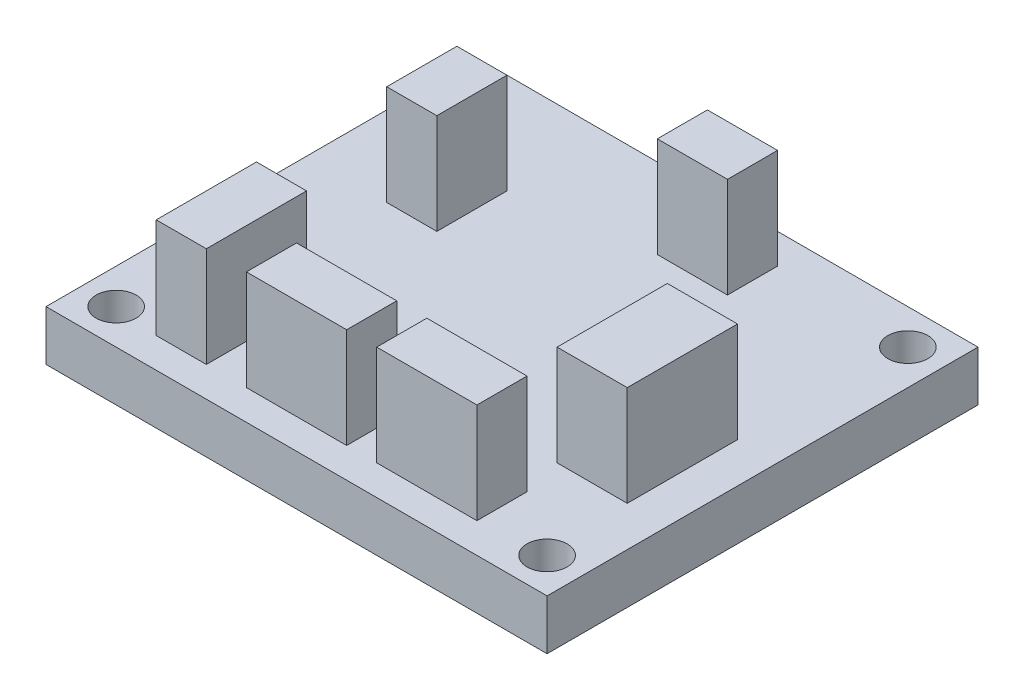
SolidWorks part; units mm, degrees
ref_plane "Plan de face" through (0, 0, 0) normal (0, 0, 1) x (1, 0, 0)
ref_plane "Plan de dessus" through (0, 0, 0) normal (0, 1, 0) x (1, 0, 0)
ref_plane "Plan de droite" through (0, 0, 0) normal (1, 0, 0) x (0, 0, -1)
sketch "Esquisse1" plane through (0, 0, 0) normal (0, 1, 0) x (1, 0, 0)
  line L0 (-25, 0) -> (0, 0) construction
  line L1 (-25, -21.5) -> (25, -21.5)
  line L2 (-25, -21.5) -> (-25, 21.5)
  line L3 (-25, 21.5) -> (25, 21.5)
  line L4 (25, -21.5) -> (25, 21.5)
  line L7 (0, 0) -> (0, 21.5) construction
  circle A0 centre (-21.5, 18) radius 2
  circle A1 centre (21.5, 18) radius 2
  circle A2 centre (21.5, -18) radius 2
  circle A3 centre (-21.5, -18) radius 2
  circle A4 centre (-21.5, 18) radius 3.5 construction
  dimension "D3" = 4
  dimension "D4" = 3.5
  dimension "D5" = 36
  dimension "D6" = 43
  dimension "D1" = 43
  dimension "D2" = 50
extrude "Boss.-Extru.1" add sketch "Esquisse1" along normal blind 5
sketch "Esquisse2" plane through (0, 0, 0) normal (0, 1, 0) x (1, 0, 0)
  line L0 (-25, -21.5) -> (25, -21.5) construction
  line L1 (-17, -8.5) -> (-12, -8.5)
  line L2 (-17, -8.5) -> (-17, -18.5)
  line L3 (-17, -18.5) -> (-12, -18.5)
  line L4 (-12, -8.5) -> (-12, -18.5)
  line L5 (-17, 11.5) -> (-12, 11.5)
  line L6 (-17, 11.5) -> (-17, 4.5)
  line L7 (-17, 4.5) -> (-12, 4.5)
  line L8 (-12, 11.5) -> (-12, 4.5)
  line L9 (1, 18.5) -> (8, 18.5)
  line L10 (1, 18.5) -> (1, 13.5)
  line L11 (1, 13.5) -> (8, 13.5)
  line L12 (8, 18.5) -> (8, 13.5)
  line L13 (14, 1.5) -> (21, 1.5)
  line L14 (14, 1.5) -> (14, -9.5)
  line L15 (14, -9.5) -> (21, -9.5)
  line L16 (21, 1.5) -> (21, -9.5)
  line L17 (15, -13.5) -> (5, -13.5)
  line L18 (15, -13.5) -> (15, -18.5)
  line L19 (15, -18.5) -> (5, -18.5)
  line L20 (5, -13.5) -> (5, -18.5)
  line L21 (2, -18.5) -> (-8, -18.5)
  line L22 (2, -18.5) -> (2, -13.5)
  line L23 (2, -13.5) -> (-8, -13.5)
  line L24 (-8, -18.5) -> (-8, -13.5)
  line L25 (25, -21.5) -> (25, 21.5) construction
  line L26 (25, 21.5) -> (-25, 21.5) construction
  dimension "D1" = 3
  dimension "D2" = 10
  dimension "D3" = 3
  dimension "D4" = 10
  dimension "D5" = 4
  dimension "D6" = 5
  dimension "D7" = 10
  dimension "D8" = 7
  dimension "D9" = 3
  dimension "D10" = 17
  dimension "D11" = 7
  dimension "D12" = 11
  dimension "D13" = 4
  dimension "D14" = 12
extrude "Boss.-Extru.2" add sketch "Esquisse2" along normal blind 15
